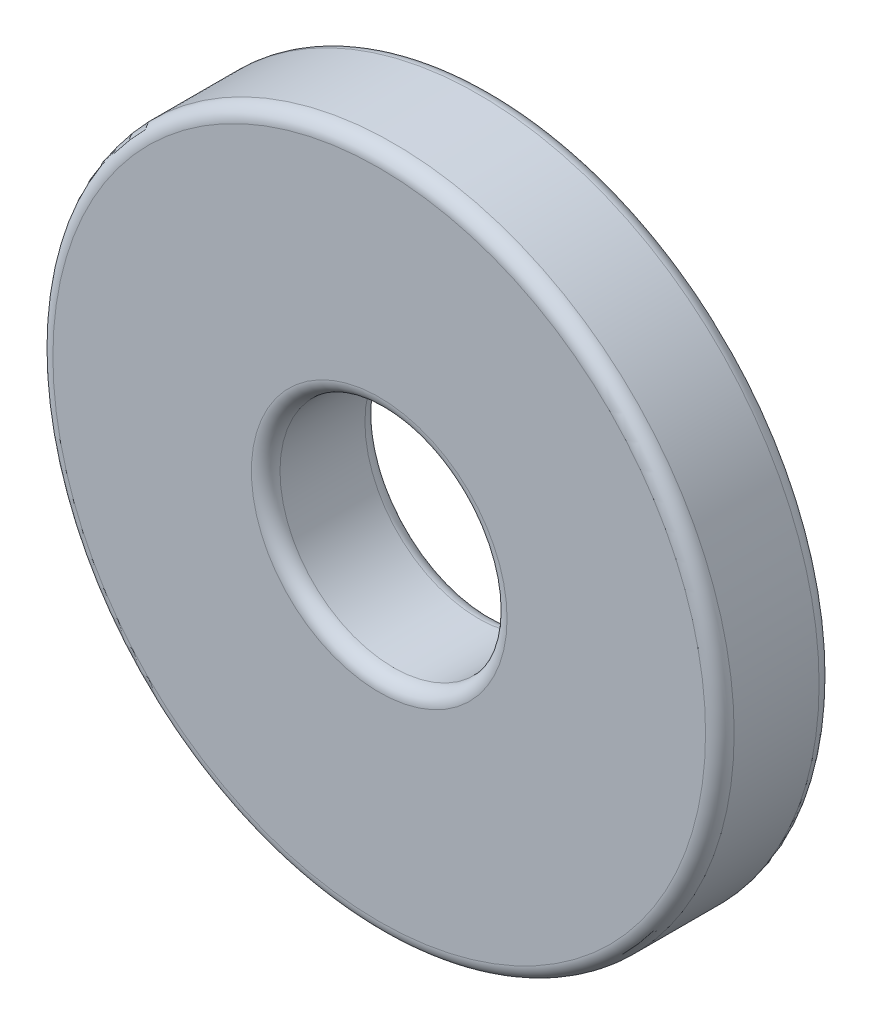
SolidWorks part; units mm, degrees
ref_plane "Front Plane" through (0, 0, 0) normal (0, 0, 1) x (1, 0, 0)
ref_plane "Top Plane" through (0, 0, 0) normal (0, 1, 0) x (1, 0, 0)
ref_plane "Right Plane" through (0, 0, 0) normal (1, 0, 0) x (0, 0, -1)
sketch "Sketch1" plane through (0, 0, 0) normal (0, 0, 1) x (1, 0, 0)
  circle A0 centre (68.3982, 3.2144) radius 4.7625
  dimension "D1" = 9.525
extrude "Boss-Extrude1" add sketch "Sketch1" along normal blind 1.5875
sketch "Sketch2" plane through (0, 0, 0) normal (0, 0, -1) x (-1, 0, 0)
  circle A0 centre (-68.3982, 3.2144) radius 1.5875
  dimension "D1" = 3.175
extrude "Cut-Extrude1" cut sketch "Sketch2" against normal through all
fillet "Fillet1" radius 0.2 3 edges at (66.8107, 3.2144, 0) (73.1607, 3.2144, 1.5875) (66.8107, 3.2144, 1.5875)
fillet "Fillet2" radius 0.2 1 edges at (73.1607, 3.2144, 0)
